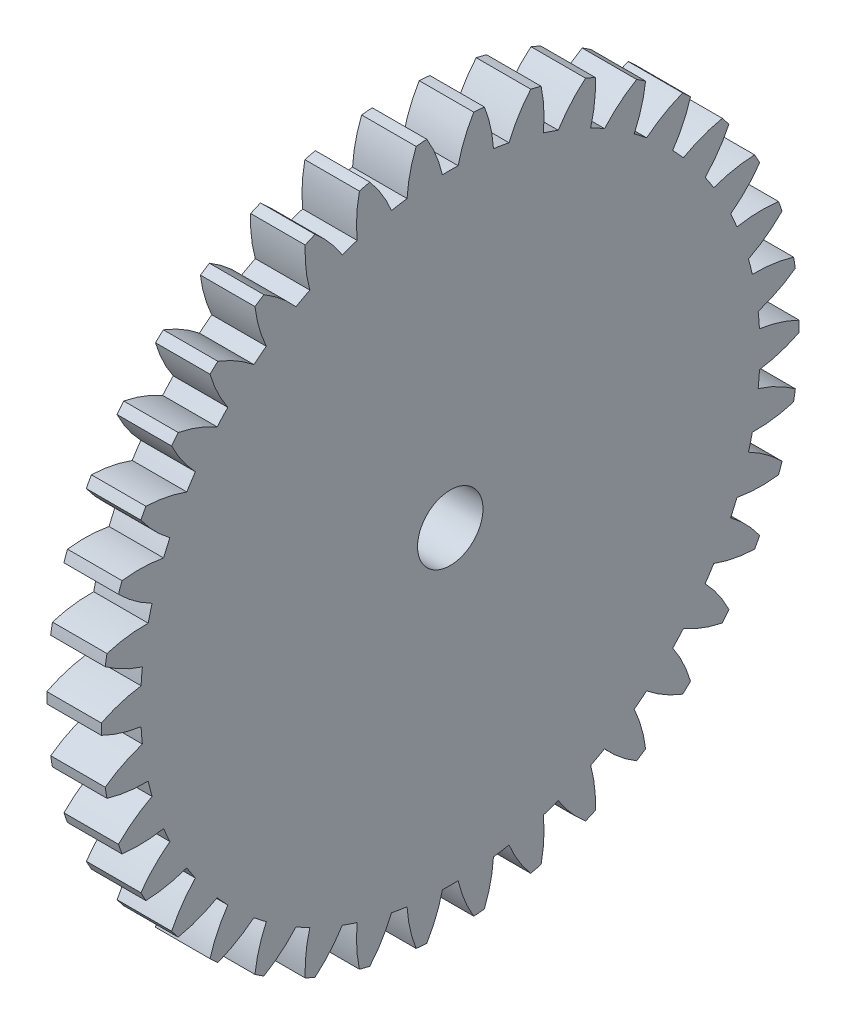
SolidWorks part; units mm, degrees
ref_plane "Plane1" through (0, 0, 0) normal (0, 0, 1) x (1, 0, 0)
ref_plane "Plane2" through (0, 0, 0) normal (0, 1, 0) x (1, 0, 0)
ref_plane "Plane3" through (0, 0, 0) normal (1, 0, 0) x (0, 0, -1)
sketch "HoldingSke" plane through (0, 0, 0) normal (0, 1, 0) x (1, 0, 0)
  line L0 (0, 0) -> (0.985, -0.7696)
  line L1 (-15, 0) -> (100, 0) construction
  line L2 (0, 0) -> (-2.1039, 2.3779)
  line L3 (0, 0) -> (-11.863, 4.5341)
  line L4 (0, 0) -> (6.8053, 5.3169)
  line L5 (0, 0) -> (-46.8476, -17.4728)
  line L6 (0, 0) -> (-2.0724, -1.3983)
  line L7 (-2.1039, 2.3779) -> (8.6586, 51.2059)
  line L8 (-76.2, 54.61) -> (-75.7, 54.61)
  line L9 (-71.009, 38.7566) -> (-53.1078, 45.2721)
  line L10 (-76.2, 71.12) -> (104.1128, 71.12)
  line L11 (0, 0) -> (-2.5, 0)
  line L12 (-76.2, 101.6) -> (-76.17, 101.6)
  line L13 (24.9733, 27.94) -> (52.9518, 28.4284)
  line L14 (24.9733, 27.94) -> (24.9743, 27.94)
  line L15 (24.9733, 27.94) -> (100.4006, 29.5858)
  line L16 (-63.627, -0.8) -> (-12.827, -0.8)
  circle A0 centre (0, 0) radius 1.5
  circle A1 centre (0, 0) radius 14.199
  circle A2 centre (0, 0) radius 37.5
  circle A3 centre (0, 0) radius 1.5
  dimension "MHD" = 28.398
  dimension "Hub_dia" = 75
  dimension "Bore" = 3
  dimension "MBD" = 3
  dimension "Num_teeth" = 38
  dimension "Pitch" = 1.25
  dimension "Overall_len" = 50
  dimension "Show_teeth" = 38
  dimension "Thickness" = 2.5
  dimension "OAL" = 50.0001
  dimension "T_dim" = 0.5
  dimension "Ap" = 20
  dimension "H" = 19.05
  dimension "Pitch_radius" = 180.3128
  dimension "Width" = 2.5
  dimension "Backlash" = 0.03
  dimension "Addendum_fac" = 1
  dimension "Dedendum_fac" = 1.25
  dimension "Clearance_fac" = 0.25
  dimension "Dedendum_add" = 0.001
  dimension "Module" = 0.8
sketch "BasProSke" plane through (0, 0, 0) normal (0, 1, 0) x (1, 0, 0)
  line L0 (-10, 0) -> (60, 0) construction
  line L1 (0, 0) -> (0, 16)
  line L2 (0, 0) -> (2.5, 0)
  line L3 (2.5, 0) -> (2.5, 16)
  line L4 (2.5, 16) -> (0, 16)
  dimension "Thickness" = 2.5
  dimension "Diameter" = 32
revolve "Base-Revolve" add sketch "BasProSke" angle 360 about L0
sketch "TooCutSke" plane through (0, 0, 0) normal (1, 0, 0) x (0, 0, -1)
  line L1 (0, 0) -> (0, 107) construction
  line L2 (0, 0) -> (-0.6806, 15.1848) construction
  line L3 (0, 0) -> (-2.5086, 30.2744) construction
  line L4 (-0.6806, 15.1848) -> (-1.2543, 15.1372) construction
  arc A0 (0.3605, 14.1944) -> (-0.3605, 14.1944) centre (0, 0) ccw
  arc A1 (1.0914, 15.9882) -> (-1.0914, 15.9882) centre (0, 0) ccw
  circle A2 centre (0, 0) radius 15.2 construction
  circle A3 centre (0, 0) radius 14.2833 construction
  arc A4 (-0.3605, 14.1944) -> (-1.0914, 15.9882) centre (-6.2846, 12.8264) ccw
  arc A5 (1.0914, 15.9882) -> (0.3605, 14.1944) centre (6.2846, 12.8264) ccw
  dimension "Root_dia" = 28.398
  dimension "Overcut_dia" = 32.0508
  dimension "Pitch_dia" = 30.4
  dimension "Base_dia" = 28.5667
  dimension "Flank_rad" = 6.08
  dimension "Half_ang" = 4.737
  dimension "Half_CT" = 0.5756
extrude "ToothCut" cut sketch "TooCutSke" along normal through all
fillet "Breaks" [suppressed] radius 0.016
fillet "RootFillets" [suppressed] radius 0.201
pattern_circular "TeethCuts" count 38 every 9.474 about axis through (-10, 0, 0) along (1, 0, 0) of "ToothCut", "RootFillets", "Breaks"
sketch "HubNeaOneSke" plane through (0, 0, 0) normal (-1, 0, 0) x (0, 0, 1)
  circle A0 centre (0, 0) radius 14.199
  dimension "Diameter" = 28.398
extrude "HubNearOne" [suppressed] add sketch "HubNeaOneSke" along normal blind 47.5001
sketch "HubNeaBotSke" plane through (0, 0, 0) normal (-1, 0, 0) x (0, 0, 1)
  circle A0 centre (0, 0) radius 14.199
  dimension "Diameter" = 28.398
extrude "HubNearBoth" [suppressed] add sketch "HubNeaBotSke" along normal blind 23.75
ref_plane "FarPln" through (2.5, 0, 0) normal (1, 0, 0) x (0, 0, -1)
sketch "HubFarSke" plane through (2.5, 0, 0) normal (1, 0, 0) x (0, 0, -1)
  circle A0 centre (0, 0) radius 14.199
  dimension "Diameter" = 28.398
extrude "HubFar" [suppressed] add sketch "HubFarSke" along normal blind 23.75
sketch "BorSke" plane through (0, 0, 0) normal (1, 0, 0) x (0, 0, -1)
  circle A0 centre (0, 0) radius 1.5
  dimension "Diameter" = 3
extrude "Bore" cut sketch "BorSke" along normal mid plane 100.0001
sketch "KeySke" plane through (0, 0, 0) normal (1, 0, 0) x (0, 0, -1)
  line L0 (-0.6, 0) -> (-0.6, 2)
  line L1 (-0.6, 2) -> (0.6, 2)
  line L2 (0.6, 2) -> (0.6, 0)
  line L3 (0, 0) -> (0, 34) construction
  line L4 (-0.6, 0) -> (0.6, 0)
  dimension "Offset" = 2
  dimension "Width" = 1.2
extrude "Keyway" [suppressed] cut sketch "KeySke" along normal mid plane 100.0001
pattern_circular "Keyway2" [suppressed] count 2 every 90 about axis through (-10, 0, 0) along (1, 0, 0)
equation "' \"Module@HoldingSke\" = 6.35"
equation "' \"Num_teeth@HoldingSke\" = 12"
equation "' \"Ap@HoldingSke\" =  20"
equation "' \"Ap@HoldingSke\" = 20"
equation "' \"Width@HoldingSke\" = 0.5 * 25.4"
equation "' \"Hub_dia@HoldingSke\"= 1 * 25.4"
equation "' \"Hub_dia@HoldingSke\" = 1 * 25.4"
equation "' \"Overall_len@HoldingSke\" = 1.0 * 25.4"
equation "' \"Bore@HoldingSke\" = 0.75 * 25.4"
equation "' \"T_dim@HoldingSke\" = 0.1 * 25.4"
equation "' \"Width@KeySke\" = 0.25 * 25.4"
equation "' \"Show_teeth@HoldingSke\" = 13"
equation "' \"Backlash@HoldingSke\" = 0.009 * 25.4"
equation "' \"Addendum_fac@HoldingSke\" = 1.0"
equation "' \"Dedendum_fac@HoldingSke\" = 1.25"
equation "' \"Dedendum_add@HoldingSke\" = 0.00005 * 25.4"
equation "' \"Clearance_fac@HoldingSke\" = 0.25"
equation "\"Pitch@HoldingSke\" = 1 / \"Module@HoldingSke\""
equation "\"Overcut_dia@TooCutSke\" = (\"Num_teeth@HoldingSke\" + 2 * \"Addendum_fac@HoldingSke\") / \"Pitch@HoldingSke\" + 0.002 * 25.4"
equation "\"Pitch_dia@TooCutSke\" = \"Num_teeth@HoldingSke\" / \"Pitch@HoldingSke\""
equation "\"Base_dia@TooCutSke\" = \"Num_teeth@HoldingSke\" / \"Pitch@HoldingSke\" * cos((\"Ap@HoldingSke\"  * 3.14159265 / 180))"
equation "\"Root_dia@TooCutSke\" = (\"Num_teeth@HoldingSke\" + 2) / \"Pitch@HoldingSke\" - 2 * (\"Addendum_fac@HoldingSke\" + \"Dedendum_fac@HoldingSke\") / \"Pitch@HoldingSke\" - \"Dedendum_add@HoldingSke\" * 2"
equation "\"Half_ang@TooCutSke\" = 180 / \"Num_teeth@HoldingSke\""
equation "\"Half_CT@TooCutSke\" = \"Num_teeth@HoldingSke\" / \"Pitch@HoldingSke\" * sin((3.14159265 / 2 / \"Num_teeth@HoldingSke\")) / 2 - 7 * \"Backlash@HoldingSke\" / 4"
equation "\"Flank_rad@TooCutSke\" = \"Num_teeth@HoldingSke\" / \"Pitch@HoldingSke\" / 5"
equation "\"Radius@RootFillets\" = \"Clearance_fac@HoldingSke\" / \"Pitch@HoldingSke\" + \"Dedendum_add@HoldingSke\""
equation "\"Break_rad@Breaks\" = 0.02 / \"Pitch@HoldingSke\""
equation "\"Thickness@HoldingSke\" = \"Width@HoldingSke\""
equation "\"OAL@HoldingSke\" = \"Thickness@HoldingSke\""
equation "\"MHD@HoldingSke\" = (\"Num_teeth@HoldingSke\" + 2) / \"Pitch@HoldingSke\" - 2 * (\"Addendum_fac@HoldingSke\" + \"Dedendum_fac@HoldingSke\")  / \"Pitch@HoldingSke\" - \"Dedendum_add@HoldingSke\" * 2"
equation "\"MBD@HoldingSke\" = (\"Num_teeth@HoldingSke\" + 2) / \"Pitch@HoldingSke\" - 2 * (\"Addendum_fac@HoldingSke\" + \"Dedendum_fac@HoldingSke\")  / \"Pitch@HoldingSke\" - \"Dedendum_add@HoldingSke\" * 2 - 0.002 * 25.4"
equation "\"MHD@HoldingSke\" = ((sgn( \"MHD@HoldingSke\" - \"Hub_dia@HoldingSke\" )-1)*( \"MHD@HoldingSke\" - \"Hub_dia@HoldingSke\" ))/-2+ \"Hub_dia@HoldingSke\""
equation "\"MBD@HoldingSke\" = ((sgn( \"MBD@HoldingSke\" - \"Bore@HoldingSke\" )-1)*( \"MBD@HoldingSke\" - \"Bore@HoldingSke\" ))/-2+ \"Bore@HoldingSke\""
equation "\"OAL@HoldingSke\" = ((sgn( \"OAL@HoldingSke\" - \"Overall_len@HoldingSke\" )+1)*( \"OAL@HoldingSke\" - \"Overall_len@HoldingSke\" ))/2 + \"Overall_len@HoldingSke\" + 0.000002 * 25.4"
equation "\"Num_teeth@TeethCuts\" = int( \"Show_teeth@HoldingSke\" ) + 1"
equation "\"Num_teeth@TeethCuts\" = ((sgn( \"Num_teeth@TeethCuts\" - \"Num_teeth@HoldingSke\" )-1)*( \"Num_teeth@TeethCuts\" - \"Num_teeth@HoldingSke\" ))/-2+ \"Num_teeth@HoldingSke\""
equation "\"Num_teeth@TeethCuts\" = ((sgn( \"Num_teeth@TeethCuts\" - 2.0)+1)*( \"Num_teeth@TeethCuts\" - 2.0))/2 +2.0"
equation "\"Angle@TeethCuts\" = 360.0 / \"Num_teeth@HoldingSke\""
equation "\"Diameter@BasProSke\" = (\"Num_teeth@HoldingSke\" + 2 * \"Addendum_fac@HoldingSke\") / \"Pitch@HoldingSke\""
equation "\"Thickness@BasProSke\"  = \"Thickness@HoldingSke\""
equation "' \"Fillet_rad@BasProSke\" =  \"Thickness@HoldingSke\" * 0.05"
equation "' \"Fillet_rad@BasProSke\" = \"Thickness@HoldingSke\" * 0.05"
equation "\"MHD@HoldingSke\" = ((sgn( \"MHD@HoldingSke\" - \"Root_dia@TooCutSke\" )-1)*( \"MHD@HoldingSke\" - \"Root_dia@TooCutSke\" ))/-2+ \"Root_dia@TooCutSke\""
equation "\"Diameter@HubNeaOneSke\" = \"MHD@HoldingSke\""
equation "\"Length@HubNearOne\" = \"OAL@HoldingSke\" - \"Thickness@BasProSke\""
equation "\"Diameter@HubNeaBotSke\" = \"MHD@HoldingSke\""
equation "\"Length@HubNearBoth\" = ( \"OAL@HoldingSke\" - \"Thickness@BasProSke\" ) / 2.0"
equation "\"Thickness@FarPln\" = \"Thickness@BasProSke\""
equation "\"Diameter@HubFarSke\" = \"MHD@HoldingSke\""
equation "\"Length@HubFar\" = ( \"OAL@HoldingSke\" - \"Thickness@BasProSke\" ) / 2.0"
equation "\"Diameter@BorSke\" = \"MBD@HoldingSke\""
equation "\"D1@Bore\" = \"OAL@HoldingSke\" * 2.0"
equation "\"D1@Keyway\" = \"OAL@HoldingSke\" * 2.0"
equation "\"Offset@KeySke\" = \"T_dim@HoldingSke\" + \"MBD@HoldingSke\" / 2.0"
